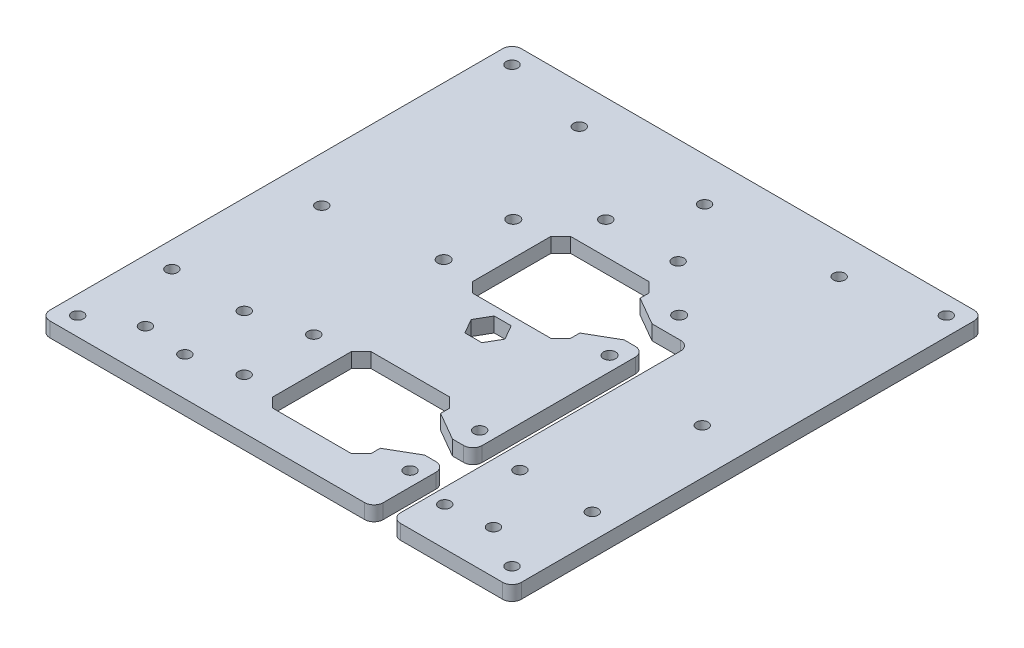
SolidWorks part; units mm, degrees
ref_plane "Plan de face" through (0, 0, 0) normal (0, 0, 1) x (1, 0, 0)
ref_plane "Plan de dessus" through (0, 0, 0) normal (0, 1, 0) x (1, 0, 0)
ref_plane "Plan de droite" through (0, 0, 0) normal (1, 0, 0) x (0, 0, -1)
sketch "Esquisse1" plane through (0, 0, 0) normal (0, 1, 0) x (1, 0, 0)
  line L1 (-101.6, -101.6) -> (101.6, -101.6)
  line L2 (-101.6, -101.6) -> (-101.6, 101.6)
  line L3 (-101.6, 101.6) -> (101.6, 101.6)
  line L4 (101.6, -101.6) -> (101.6, 101.6)
  line L5 (-101.6, -101.6) -> (101.6, 101.6) construction
  line L6 (-101.6, 101.6) -> (101.6, -101.6) construction
  point P0 (0, 0)
  dimension "D1" = 203.2
extrude "Boss.-Extru.1" add sketch "Esquisse1" along normal blind 6.35
sketch "Esquisse2" plane through (0, 6.35, 0) normal (0, 1, 0) x (1, 0, 0)
  circle A0 centre (-35.6, -49.85) radius 2.5
  circle A1 centre (-35.6, -79.85) radius 2.5
  circle A2 centre (35.9, -79.85) radius 2.5
  circle A3 centre (35.9, -49.85) radius 2.5
extrude "Enlèv. mat.-Extru.1" cut sketch "Esquisse2" against normal through all
sketch "Esquisse3" plane through (0, 6.35, 0) normal (0, 1, 0) x (1, 0, 0)
  circle A0 centre (-93.6, 93.6) radius 2.5
  circle A1 centre (93.6, 93.6) radius 2.5
  circle A2 centre (93.6, -93.6) radius 2.5
  circle A3 centre (-93.6, -93.6) radius 2.5
extrude "Enlèv. mat.-Extru.2" cut sketch "Esquisse3" against normal through all
sketch "Esquisse4" plane through (0, 6.35, 0) normal (0, 1, 0) x (1, 0, 0)
  circle A0 centre (15.5885, 56) radius 2.5
  circle A1 centre (-15.5885, 56) radius 2.5
  circle A2 centre (0, 83) radius 2.5
  circle A3 centre (-75, -83) radius 2.5
  circle A4 centre (-90.5885, -56) radius 2.5
  circle A5 centre (-59.4115, -56) radius 2.5
  circle A6 centre (59.413, -55.9992) radius 2.5
  circle A7 centre (90.5899, -55.9992) radius 2.5
  circle A8 centre (75.0015, -82.9992) radius 2.5
extrude "Enlèv. mat.-Extru.3" cut sketch "Esquisse4" against normal through all
sketch "Esquisse6" plane through (0, 0, 0) normal (0, -1, 0) x (1, 0, 0)
  line L0 (-56, 85) -> (-56, -85) construction
  circle A0 centre (-56, 85) radius 2.5
  circle A1 centre (-56, -85) radius 2.5
  circle A2 centre (-82, 0) radius 2.5
  point P6 (-56, 0)
  dimension "D1" = 5
  dimension "D2" = 82
  dimension "D3" = 85
  dimension "D4" = 56
extrude "Enlèv. mat.-Extru.5" cut sketch "Esquisse6" against normal through all
mirror "Symétrie1" about plane through (0, 0, 0) normal (1, 0, 0) of "Enlèv. mat.-Extru.5"
sketch "Esquisse8" plane through (0, 6.35, 0) normal (0, 1, 0) x (1, 0, 0)
  circle A0 centre (75, -65) radius 3.925
  circle A1 centre (75, -65) radius 3.925 construction
sketch "Esquisse11" plane through (0, 6.35, 0) normal (0, 1, 0) x (1, 0, 0)
  line L0 (-16.9781, 42.15) -> (16.9781, 42.15)
  line L1 (16.9781, 42.15) -> (21.15, 37.9781)
  line L2 (21.15, 37.9781) -> (21.15, 4.0219)
  line L3 (21.15, 4.0219) -> (16.9781, -0.15)
  line L4 (16.9781, -0.15) -> (-16.9781, -0.15)
  line L5 (-16.9781, -0.15) -> (-21.15, 4.0219)
  line L6 (-21.15, 4.0219) -> (-21.15, 37.9781)
  line L7 (-21.15, 37.9781) -> (-16.9781, 42.15)
  line L8 (21.15, 4.0219) -> (21.15, 37.9781) construction
  line L9 (-21.15, 4.0219) -> (-16.9781, -0.15) construction
  line L10 (-21.15, 37.9781) -> (-21.15, 4.0219) construction
  line L11 (-16.9781, 42.15) -> (-21.15, 37.9781) construction
extrude "Enlèv. mat.-Extru.9" cut sketch "Esquisse11" against normal through all
sketch "Esquisse5" plane through (0, 6.35, 0) normal (0, 1, 0) x (1, 0, 0)
  line L0 (101.6, 101.6) -> (-101.6, 101.6) construction
  line L1 (3.6517, -4) -> (-3.6517, -4)
  line L2 (-3.6517, -4) -> (-7.3035, -10.325)
  line L3 (-7.3035, -10.325) -> (-3.6517, -16.65)
  line L4 (-3.6517, -16.65) -> (3.6517, -16.65)
  line L5 (3.6517, -16.65) -> (7.3035, -10.325)
  line L6 (7.3035, -10.325) -> (3.6517, -4)
  circle A0 centre (0, -10.325) radius 6.325 construction
  dimension "D1" = 12.65
  dimension "D2" = 4
extrude "Enlèv. mat.-Extru.4" cut sketch "Esquisse5" against normal through all
sketch "Esquisse9" plane through (0, 6.35, 0) normal (0, 1, 0) x (1, 0, 0)
  line L0 (-16.9781, -43.85) -> (16.9781, -43.85)
  line L1 (16.9781, -43.85) -> (21.15, -48.0219)
  line L2 (21.15, -48.0219) -> (21.15, -81.9781)
  line L3 (21.15, -81.9781) -> (16.9781, -86.15)
  line L4 (16.9781, -86.15) -> (-16.9781, -86.15)
  line L5 (-16.9781, -86.15) -> (-21.15, -81.9781)
  line L6 (-21.15, -81.9781) -> (-21.15, -48.0219)
  line L7 (-21.15, -48.0219) -> (-16.9781, -43.85)
  point P4 (21.15, -65)
  point P9 (-21.15, -65)
  point P12 (0, -43.85)
  point P13 (0, -86.15)
  dimension "D1" = 5.9
  dimension "D2" = 42.3
  dimension "D3" = 42.3
extrude "Enlèv. mat.-Extru.7" cut sketch "Esquisse9" against normal through all
sketch "Esquisse10" plane through (0, 6.35, 0) normal (0, 1, 0) x (1, 0, 0)
  line L0 (21.15, -81.9781) -> (21.15, -48.0219) construction
  line L1 (21.15, -58.9281) -> (42.1, -58.9281)
  line L2 (21.15, -58.9281) -> (21.15, -70.9281)
  line L3 (21.15, -70.9281) -> (42.1, -70.9281)
  line L4 (49.6, -58.9281) -> (49.6, -70.9281)
  line L5 (-101.6, -101.6) -> (101.6, -101.6) construction
  line L7 (49.6, -70.9281) -> (49.6, -101.6)
  line L8 (49.6, -101.6) -> (42.1, -101.6)
  line L9 (42.1, -70.9281) -> (42.1, -101.6)
  line L10 (101.6, -101.6) -> (101.6, 101.6) construction
  line L11 (21.15, 4.0219) -> (21.15, 37.9781) construction
  line L12 (21.15, 15.0719) -> (42.1, 15.0719)
  line L13 (21.15, 15.0719) -> (21.15, 27.0719)
  line L14 (21.15, 27.0719) -> (49.6, 27.0719)
  line L15 (49.6, 15.0719) -> (49.6, 27.0719)
  line L18 (49.6, 15.0719) -> (49.6, -58.9281)
  line L20 (42.1, 15.0719) -> (42.1, -58.9281)
  dimension "D1" = 11.05
  dimension "D2" = 12
  dimension "D3" = 7.5
  dimension "D4" = 52
  dimension "D5" = 11.05
extrude "Enlèv. mat.-Extru.8" cut sketch "Esquisse10" against normal through all
fillet "Congé2" radius 4 10 edges at (101.6, 3.175, -101.6) (-101.6, 3.175, -101.6) (-101.6, 3.175, 101.6) (101.6, 3.175, 101.6) (42.1, 3.175, 70.9281) (49.6, 3.175, 101.6) (42.1, 3.175, 101.6) (42.1, 3.175, 58.9281) (42.1, 3.175, -15.0719) (49.6, 3.175, -27.0719)
sketch "Esquisse12" plane through (0, 6.35, 0) normal (0, 1, 0) x (1, 0, 0)
  circle A0 centre (-35.6, 36.15) radius 2.6
  circle A1 centre (-35.6, 6.15) radius 2.6
  circle A2 centre (35.9, 6.15) radius 2.6
  circle A3 centre (35.9, 36.15) radius 2.6
  circle A4 centre (35.9, 36.15) radius 2.6 construction
extrude "Enlèv. mat.-Extru.10" cut sketch "Esquisse12" against normal through all
chamfer "Chanfrein2" distance 7 angle 60 2 edges at (21.15, 3.175, 70.9281) (21.15, 3.175, 58.9281)
chamfer "Chanfrein3" distance 7 angle 60 2 edges at (21.15, 3.175, -15.0719) (21.15, 3.175, -27.0719)
equation "\"grosseur_nut_longue_screw\"=12.65"
equation "\"D1@Esquisse5\"=\"grosseur_nut_longue_screw\""
